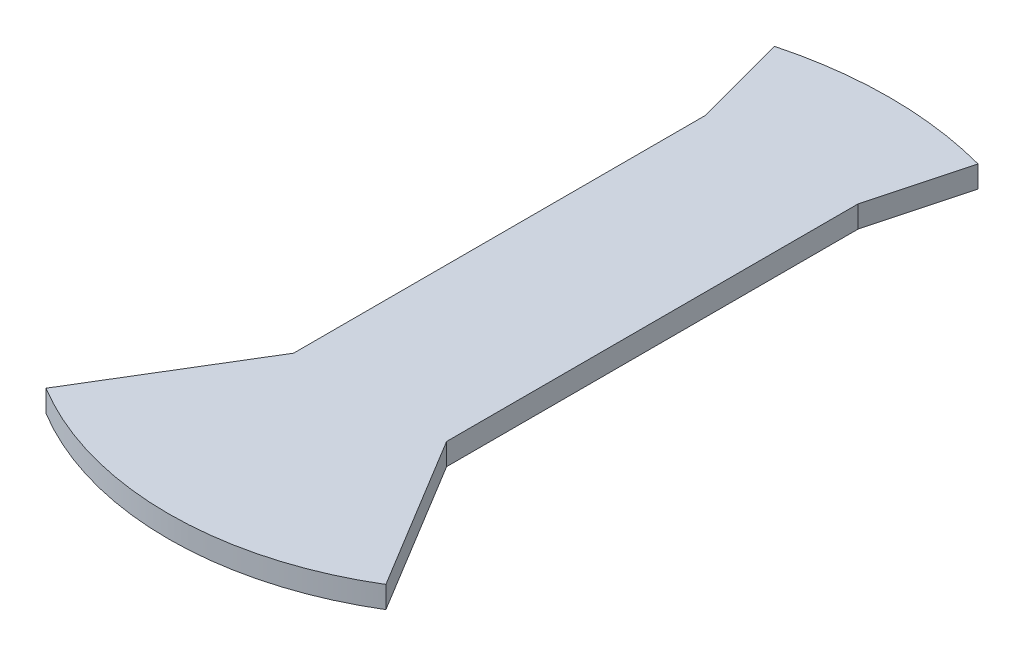
SolidWorks part; units mm, degrees
ref_plane "Front Plane" through (0, 0, 0) normal (0, 0, 1) x (1, 0, 0)
ref_plane "Top Plane" through (0, 0, 0) normal (0, 1, 0) x (1, 0, 0)
ref_plane "Right Plane" through (0, 0, 0) normal (1, 0, 0) x (0, 0, -1)
sketch "Sketch1" plane through (0, 0, 0) normal (0, 1, 0) x (1, 0, 0)
  line L0 (0, 114.3) -> (0, -114.3) construction
  line L1 (-5.7523, 21.4677) -> (-29.583, 110.4053) construction
  line L2 (-11.5221, -19.0051) -> (-49.3802, -81.4503) construction
  line L3 (11.5221, -19.0051) -> (49.3802, -81.4503) construction
  line L4 (5.7523, 21.4677) -> (29.583, 110.4053) construction
  line L5 (-22.225, 82.9448) -> (-22.225, -36.6591)
  line L6 (22.225, 82.9448) -> (22.225, -36.6591)
  line L7 (-29.583, 110.4053) -> (-22.225, 82.9448)
  line L8 (22.225, 82.9448) -> (29.583, 110.4053)
  line L9 (-22.225, -36.6591) -> (-49.3802, -81.4503)
  line L10 (22.225, -36.6591) -> (49.3802, -81.4503)
  circle A0 centre (0, 0) radius 22.225 construction
  circle A1 centre (0, 0) radius 114.3 construction
  circle A2 centre (0, 0) radius 95.25 construction
  arc A3 (-49.3802, -81.4503) -> (49.3802, -81.4503) centre (0, 0) ccw
  arc A4 (-29.583, 110.4053) -> (29.583, 110.4053) centre (0, 0) cw
  dimension "D1" = 44.45
  dimension "D2" = 30
  dimension "D3" = 228.6
  dimension "D4" = 190.5
  dimension "D5" = 62.454
extrude "Boss-Extrude1" add sketch "Sketch1" along normal mid plane 6.35
